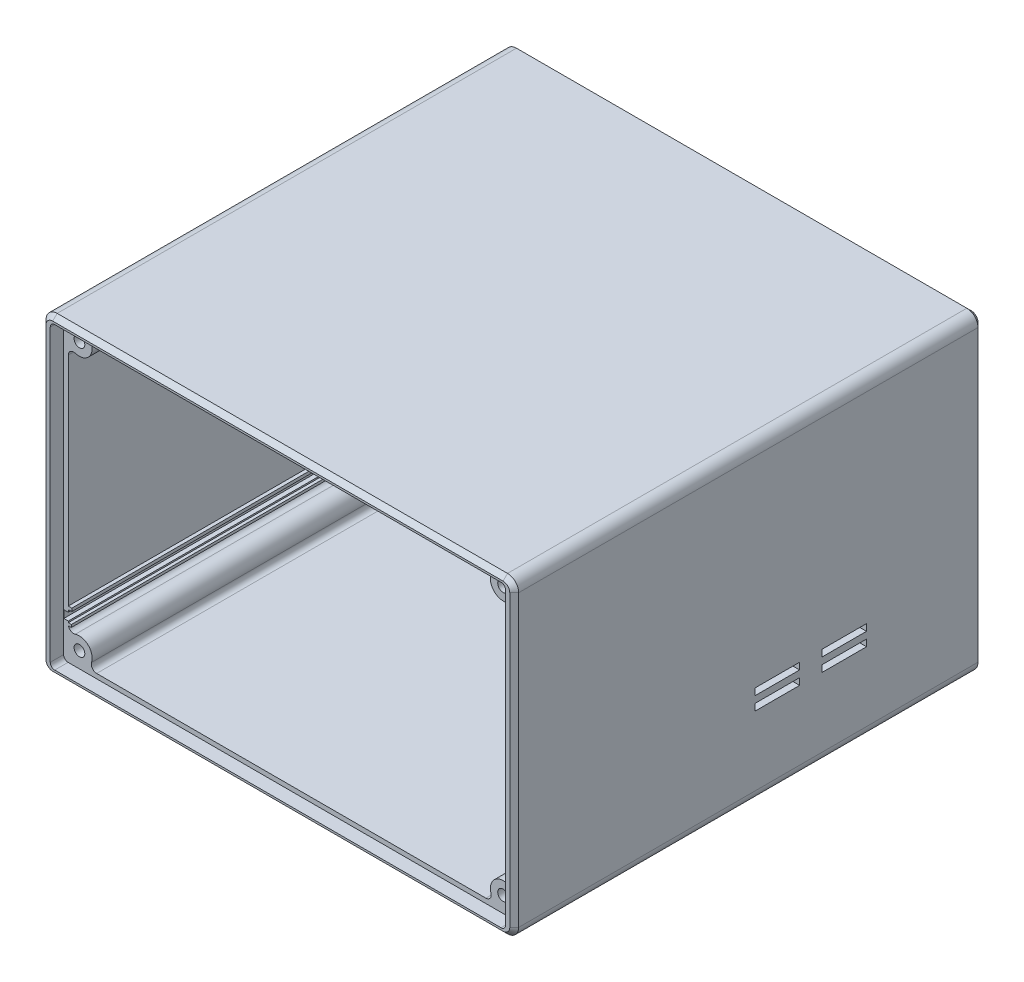
SolidWorks part; units mm, degrees
other "标注1"
sketch "草图6" plane through (106, 0, 0) normal (0.1019, -0.063, 0.9928) x (0.9807, -0.1611, -0.1109)
other "标注2"
sketch "草图12" plane through (106, 70, 0) normal (0.1813, 0.0075, 0.9834) x (0.9834, -0.0097, -0.1812)
ref_plane "前视基准面" through (0, 0, 0) normal (0, 0, 1) x (1, 0, 0)
ref_plane "上视基准面" through (0, 0, 0) normal (0, 1, 0) x (1, 0, 0)
ref_plane "右视基准面" through (0, 0, 0) normal (1, 0, 0) x (0, 0, -1)
other "Configuration Table"
sketch "草图3" plane through (0, 0, 0) normal (0, 1, 0) x (1, 0, 0)
  line L1 (0, 0) -> (106, 0)
  line L2 (0, 0) -> (0, 105)
  line L3 (0, 105) -> (106, 105)
  line L4 (106, 0) -> (106, 105)
extrude "凸台-拉伸1" add sketch "草图3" along normal blind 70
sketch "草图4" plane through (0, 0, 0) normal (0, 0, 1) x (1, 0, 0)
  line L0 (0, 70) -> (0, 0) construction
  line L1 (3, 2.5) -> (103, 2.5)
  line L2 (3, 2.5) -> (3, 67.5)
  line L3 (3, 67.5) -> (103, 67.5)
  line L4 (103, 2.5) -> (103, 67.5)
  line L6 (0, 0) -> (106, 0) construction
  line L7 (106, 70) -> (106, 0) construction
  line L8 (0, 70) -> (106, 70) construction
  dimension "D1" = 3
  dimension "D2" = 2.5
  dimension "D3" = 3
  dimension "D4" = 2.5
extrude "切除-拉伸1" cut sketch "草图4" against normal through all
fillet "圆角2" radius 2.5 4 edges at (106, 0, -52.5) (0, 0, -52.5) (106, 70, -52.5) (0, 70, -52.5)
fillet "圆角3" radius 2.5 4 edges at (103, 67.5, -52.5) (103, 2.5, -52.5) (3, 67.5, -52.5) (3, 2.5, -52.5)
chamfer "倒角1" distance 1 angle 45 16 edges at (0.7322, 0.7322, -105) (0, 35, -105) (53, 0, -105) (0.7322, 69.2678, -105) (105.2678, 0.7322, -105) (53, 70, -105) (106, 35, -105) (105.2678, 69.2678, -105) (105.2678, 69.2678, 0) (106, 35, 0) (105.2678, 0.7322, 0) (53, 0, 0) (0.7322, 0.7322, 0) (0, 35, 0) (0.7322, 69.2678, 0) (53, 70, 0)
sketch "草图5" plane through (0, 0, 0) normal (0, 0, 1) x (1, 0, 0)
  line L1 (4.6168, 9.5) -> (2, 9.5)
  line L2 (4.6168, 9.5) -> (4.6168, 11.2)
  line L3 (4.6168, 11.2) -> (2, 11.2)
  line L4 (2, 9.5) -> (2, 11.2)
  line L5 (5.5, 2.5) -> (100.5, 2.5) construction
  line L6 (0, 2.5) -> (0, 67.5) construction
  line L7 (104, 9.5) -> (101.3832, 9.5)
  line L8 (104, 9.5) -> (104, 11.2)
  line L9 (104, 11.2) -> (101.3832, 11.2)
  line L10 (101.3832, 9.5) -> (101.3832, 11.2)
  line L11 (106, 67.5) -> (106, 2.5) construction
  point P6 (2, 10.35)
  dimension "D1" = 1.7
  dimension "D2" = 7
  dimension "D3" = 2
  dimension "D4" = 1.7
  dimension "D5" = 2
  dimension "D6" = 7
extrude "切除-拉伸2" cut sketch "草图5" against normal through all
sketch "草图7" plane through (0, 0, 0) normal (0, 0, 1) x (1, 0, 0)
  line L0 (103.5, 0) -> (2.5, 0) construction
  line L1 (1.95, 1.45) -> (104.05, 1.45)
  line L2 (1.95, 1.45) -> (1.95, 68.55)
  line L3 (1.95, 68.55) -> (104.05, 68.55)
  line L4 (104.05, 1.45) -> (104.05, 68.55)
  line L5 (0, 2.5) -> (0, 67.5) construction
  line L6 (106, 67.5) -> (106, 2.5) construction
  line L7 (2.5, 70) -> (103.5, 70) construction
  dimension "D1" = 1.45
  dimension "D2" = 1.95
  dimension "D3" = 1.95
  dimension "D4" = 1.45
extrude "切除-拉伸3" cut sketch "草图7" against normal blind 3
fillet "圆角4" radius 1 4 edges at (1.95, 1.45, -1.5) (104.05, 1.45, -1.5) (104.05, 68.55, -1.5) (1.95, 68.55, -1.5)
sketch "草图8" plane through (0, 0, -105) normal (0, 0, -1) x (-1, 0, 0)
  line L0 (-2.5, 0) -> (-103.5, 0) construction
  line L1 (-104.05, 68.55) -> (-1.95, 68.55)
  line L2 (-104.05, 68.55) -> (-104.05, 1.45)
  line L3 (-104.05, 1.45) -> (-1.95, 1.45)
  line L4 (-1.95, 68.55) -> (-1.95, 1.45)
  line L5 (-106, 2.5) -> (-106, 67.5) construction
  line L6 (0, 67.5) -> (0, 2.5) construction
  line L7 (-103.5, 70) -> (-2.5, 70) construction
  dimension "D1" = 1.45
  dimension "D2" = 1.95
  dimension "D3" = 1.95
  dimension "D4" = 1.45
extrude "切除-拉伸4" cut sketch "草图8" against normal blind 2
fillet "圆角5" radius 1 4 edges at (104.05, 1.45, -104) (1.95, 1.45, -104) (1.95, 68.55, -104) (104.05, 68.55, -104)
sketch "草图9" plane through (0, 0, -3) normal (0, 0, 1) x (1, 0, 0)
  line L0 (1.95, 67.55) -> (1.95, 2.45) construction
  line L2 (2.95, 1.45) -> (103.05, 1.45) construction
  line L3 (1.95, 67.55) -> (1.95, 2.45) construction
  line L4 (104.05, 2.45) -> (104.05, 67.55) construction
  line L5 (103.05, 68.55) -> (2.95, 68.55) construction
  circle A0 centre (5.45, 4.95) radius 2.9
  circle A1 centre (100.55, 4.95) radius 2.9
  circle A2 centre (100.55, 65.05) radius 2.9
  circle A3 centre (5.45, 65.05) radius 2.9
  dimension "D1" = 3.5
  dimension "D2" = 3.5
  dimension "D3" = 3.5
  dimension "D9" = 5.8
  dimension "D4" = 3.5
  dimension "D5" = 3.5
  dimension "D6" = 3.5
  dimension "D7" = 3.5
  dimension "D8" = 3.5
extrude "凸台-拉伸2" add sketch "草图9" against normal up to surface (100 mm away) up to face at (53, 35, -103)
fillet "圆角6" radius 1.2 8 edges at (103, 63.4984, -53) (98.9984, 67.5, -53) (7.0016, 67.5, -53) (3, 63.4984, -53) (103, 6.5016, -53) (98.9984, 2.5, -53) (3, 6.5016, -53) (7.0016, 2.5, -53)
sketch "草图10" plane through (0, 0, -3) normal (0, 0, 1) x (1, 0, 0)
  line L1 (2.95, 1.45) -> (103.05, 1.45) construction
  line L2 (1.95, 67.55) -> (1.95, 2.45) construction
  line L3 (103.05, 68.55) -> (2.95, 68.55) construction
  line L5 (104.05, 2.45) -> (104.05, 67.55) construction
  line L6 (104.05, 2.45) -> (104.05, 67.55) construction
  line L7 (2.95, 1.45) -> (103.05, 1.45) construction
  circle A0 centre (5.5, 5) radius 1.2
  circle A1 centre (100.5, 65) radius 1.2
  circle A2 centre (5.5, 65) radius 1.2
  circle A3 centre (100.5, 5) radius 1.2
  dimension "D1" = 2.4
  dimension "D10" = 2.4
  dimension "D11" = 2.4
  dimension "D12" = 2.4
  dimension "D2" = 3.55
  dimension "D3" = 3.55
  dimension "D4" = 3.55
  dimension "D5" = 3.55
  dimension "D6" = 3.55
  dimension "D7" = 3.55
  dimension "D8" = 3.55
  dimension "D9" = 3.55
extrude "切除-拉伸5" cut sketch "草图10" against normal through all
sketch "草图11" plane through (106, 0, 0) normal (1, 0, 0) x (0, 0, -1)
  line L0 (104, 0) -> (1, 0) construction
  line L1 (79, 18) -> (69, 18)
  line L2 (79, 18) -> (79, 19.5)
  line L3 (79, 19.5) -> (69, 19.5)
  line L4 (69, 18) -> (69, 19.5)
  line L5 (79, 21) -> (69, 21)
  line L6 (79, 21) -> (79, 22.5)
  line L7 (79, 22.5) -> (69, 22.5)
  line L8 (69, 21) -> (69, 22.5)
  line L9 (64, 18) -> (54, 18)
  line L10 (64, 18) -> (64, 19.5)
  line L11 (64, 19.5) -> (54, 19.5)
  line L12 (54, 18) -> (54, 19.5)
  line L13 (64, 21) -> (54, 21)
  line L14 (64, 21) -> (64, 22.5)
  line L15 (64, 22.5) -> (54, 22.5)
  line L16 (54, 21) -> (54, 22.5)
  line L17 (104, 2.5) -> (104, 67.5) construction
  dimension "D1" = 1.5
  dimension "D2" = 1.5
  dimension "D3" = 1.5
  dimension "D4" = 1.5
  dimension "D5" = 10
  dimension "D6" = 10
  dimension "D7" = 10
  dimension "D8" = 10
  dimension "D9" = 1.5
  dimension "D10" = 1.5
  dimension "D11" = 5
  dimension "D12" = 5
  dimension "D13" = 18
  dimension "D14" = 25
extrude "切除-拉伸6" cut sketch "草图11" against normal through all
sketch "草图13" plane through (0, 0, -3) normal (0, 0, 1) x (1, 0, 0)
  line L0 (103, 11.2) -> (103, 61.1452) construction
  line L17 (103, 11.7315) -> (102.3804, 11.7315)
  line L18 (103, 11.7315) -> (103, 12.4065)
  line L19 (103, 12.4065) -> (102.3804, 12.4065)
  line L20 (102.3804, 11.7315) -> (102.3804, 12.4065)
  line L21 (103, 8.8548) -> (103, 9.5) construction
  line L22 (103, 9.1774) -> (102.3804, 9.1774)
  line L23 (103, 9.1774) -> (103, 8.6008)
  line L24 (103, 8.6008) -> (102.3804, 8.6008)
  line L25 (102.3804, 9.1774) -> (102.3804, 8.6008)
  line L26 (3, 9.5) -> (3, 8.8548) construction
  line L27 (3, 9.1774) -> (3.6938, 9.1774)
  line L28 (3, 9.1774) -> (3, 8.6008)
  line L29 (3, 8.6008) -> (3.6938, 8.6008)
  line L30 (3.6938, 9.1774) -> (3.6938, 8.6008)
  line L31 (3, 61.1452) -> (3, 11.2) construction
  line L32 (3, 11.7315) -> (3.7956, 11.7315)
  line L33 (3, 11.7315) -> (3, 12.4065)
  line L34 (3, 12.4065) -> (3.7956, 12.4065)
  line L35 (3.7956, 11.7315) -> (3.7956, 12.4065)
extrude "凸台-拉伸3" add sketch "草图13" against normal up to surface (100 mm away) up to face at (99.3, 5, -103)
